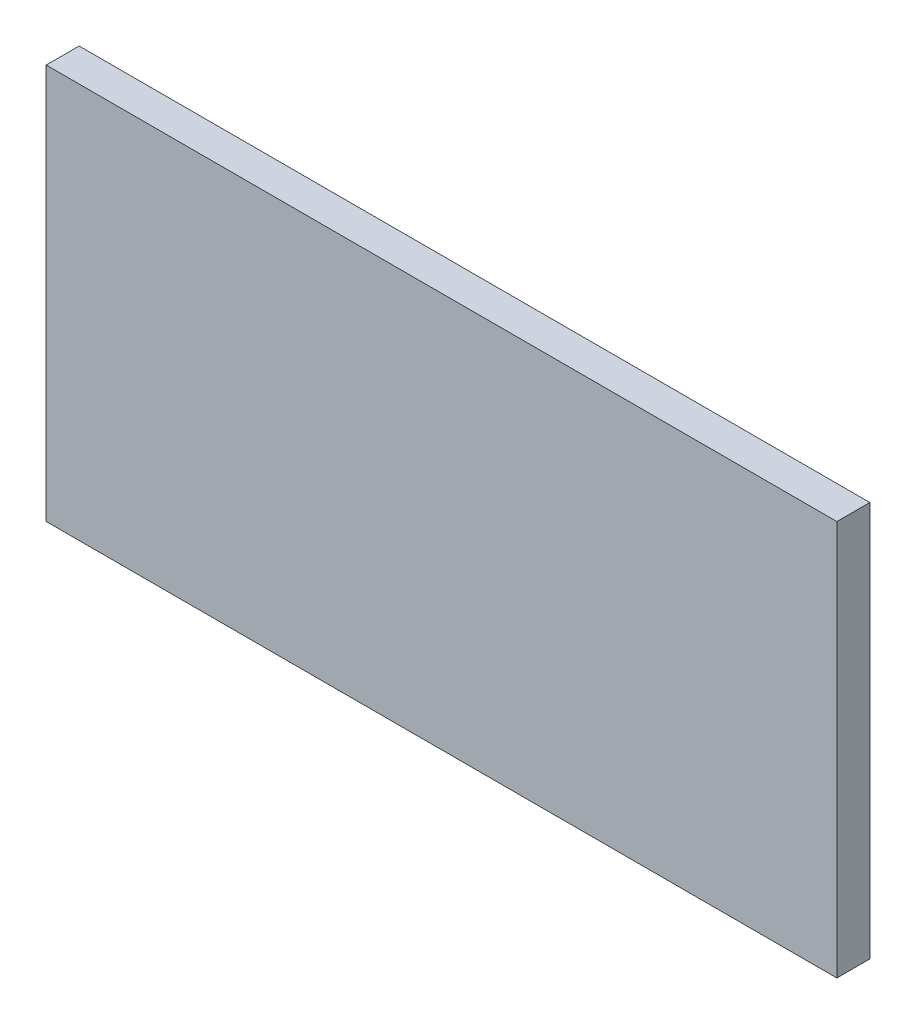
SolidWorks part; units mm, degrees
ref_plane "前视基准面" through (0, 0, 0) normal (0, 0, 1) x (1, 0, 0)
ref_plane "上视基准面" through (0, 0, 0) normal (0, 1, 0) x (1, 0, 0)
ref_plane "右视基准面" through (0, 0, 0) normal (1, 0, 0) x (0, 0, -1)
sketch "草图1" plane through (0, 0, 0) normal (0, 0, 1) x (1, 0, 0)
  line L1 (-61.762, 25.6878) -> (58.238, 25.6878)
  line L2 (-61.762, 25.6878) -> (-61.762, -34.3122)
  line L3 (-61.762, -34.3122) -> (58.238, -34.3122)
  line L4 (58.238, 25.6878) -> (58.238, -34.3122)
  dimension "D1" = 120
  dimension "D2" = 60
extrude "凸台-拉伸1" add sketch "草图1" along normal blind 5
